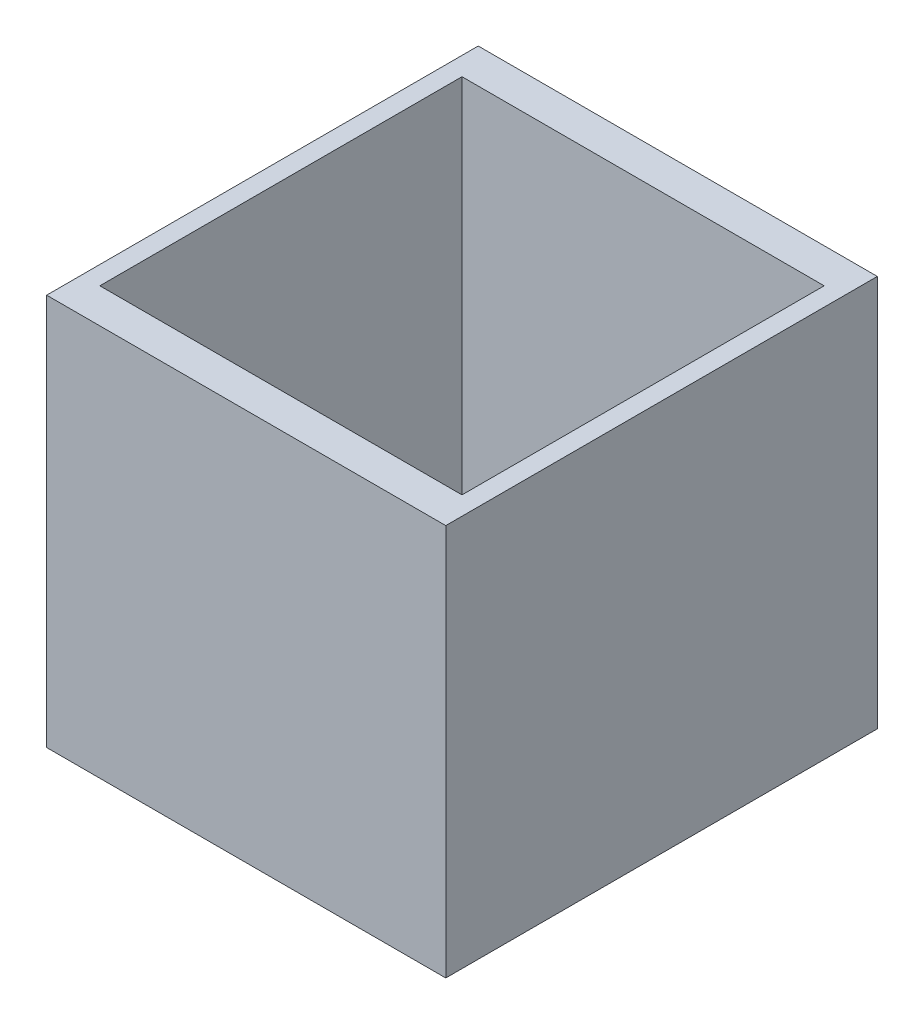
SolidWorks part; units mm, degrees
ref_plane "Front Plane" through (0, 0, 0) normal (0, 0, 1) x (1, 0, 0)
ref_plane "Top Plane" through (0, 0, 0) normal (0, 1, 0) x (1, 0, 0)
ref_plane "Right Plane" through (0, 0, 0) normal (1, 0, 0) x (0, 0, -1)
sketch "Sketch1" plane through (0, 0, 0) normal (0, 1, 0) x (1, 0, 0)
  line L1 (-11.745, 12.7) -> (11.745, 12.7)
  line L2 (-11.745, 12.7) -> (-11.745, -12.7)
  line L3 (-11.745, -12.7) -> (11.745, -12.7)
  line L4 (11.745, 12.7) -> (11.745, -12.7)
  line L5 (-11.745, 12.7) -> (11.745, -12.7) construction
  line L6 (-11.745, -12.7) -> (11.745, 12.7) construction
  line L7 (-10.6575, 10.6575) -> (10.6575, 10.6575)
  line L8 (-10.6575, 10.6575) -> (-10.6575, -10.6575)
  line L9 (-10.6575, -10.6575) -> (10.6575, -10.6575)
  line L10 (10.6575, 10.6575) -> (10.6575, -10.6575)
  line L11 (-10.6575, 10.6575) -> (10.6575, -10.6575) construction
  line L12 (-10.6575, -10.6575) -> (10.6575, 10.6575) construction
  point P0 (0, 0)
  point P6 (0, 0)
  dimension "D1" = 23.49
  dimension "D2" = 25.4
  dimension "D3" = 21.315
  dimension "D4" = 21.315
extrude "Boss-Extrude1" add sketch "Sketch1" along normal blind 23.06
